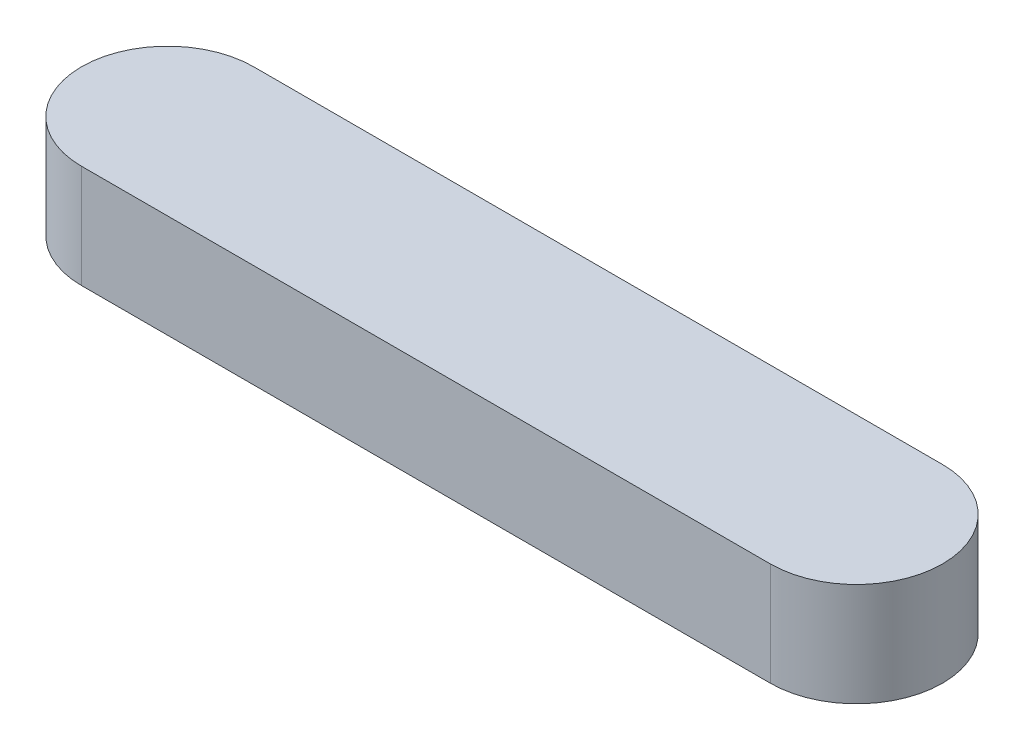
SolidWorks part; units mm, degrees
ref_plane "Front" through (0, 0, 0) normal (0, 0, 1) x (1, 0, 0)
ref_plane "Top" through (0, 0, 0) normal (0, 1, 0) x (1, 0, 0)
ref_plane "Right" through (0, 0, 0) normal (1, 0, 0) x (0, 0, -1)
sketch "Esquisse1" plane through (0, 0, 0) normal (0, 1, 0) x (1, 0, 0)
  line L0 (40, 0) -> (-40, 0) construction
  line L1 (40, -10) -> (-40, -10)
  line L2 (40, 10) -> (-40, 10)
  arc A0 (40, -10) -> (40, 10) centre (40, 0) ccw
  arc A1 (-40, 10) -> (-40, -10) centre (-40, 0) ccw
  point P2 (0, 0)
  dimension "D2" = 10
  dimension "D1" = 80
extrude "Boss.-Extru.1" add sketch "Esquisse1" along normal blind 12
